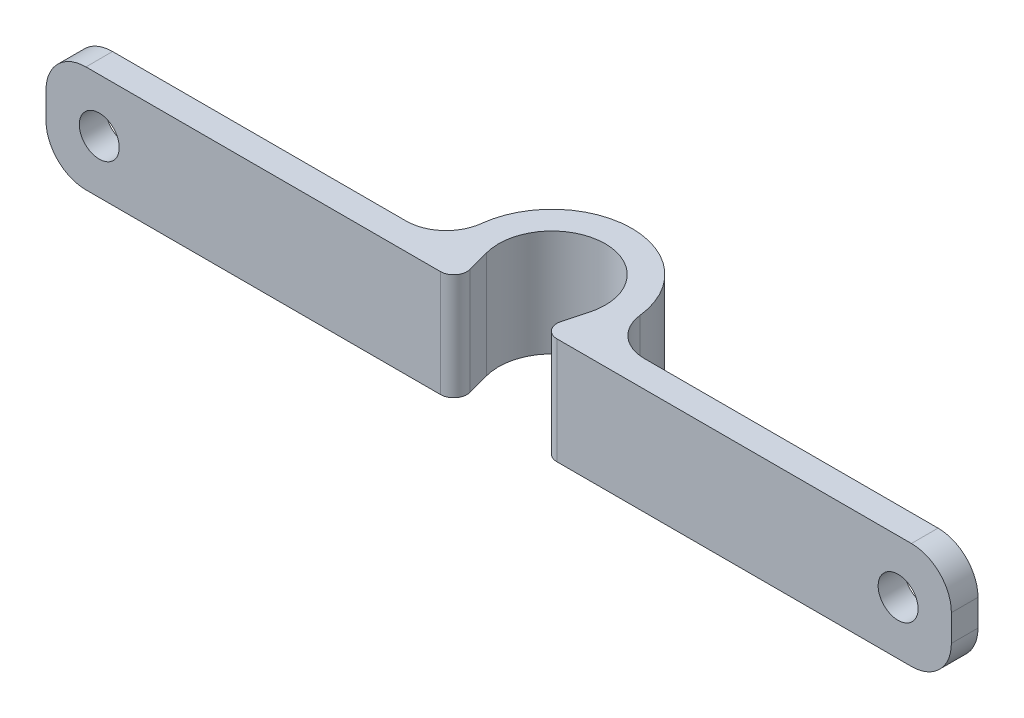
SolidWorks part; units mm, degrees
material "ABS"
ref_plane "Front" through (0, 0, 0) normal (0, 0, 1) x (1, 0, 0)
ref_plane "Top" through (0, 0, 0) normal (0, 1, 0) x (1, 0, 0)
ref_plane "Right" through (0, 0, 0) normal (1, 0, 0) x (0, 0, -1)
sketch "Esquisse1" plane through (0, 0, 0) normal (0, 1, 0) x (1, 0, 0)
  line L0 (-34, 0) -> (-3.0693, 0)
  line L1 (-3.0693, 0) -> (-3.8637, 2.9647)
  line L2 (3.8637, 2.9647) -> (3.0693, 0)
  line L3 (3.0693, 0) -> (34, 0)
  arc A0 (-3.8637, 2.9647) -> (3.8637, 2.9647) centre (0, 4) cw
  dimension "D1" = 4
  dimension "D2" = 4
  dimension "D3" = 68
  dimension "D4" = 30
extrude "Extru.-Mince1" add sketch "Esquisse1" along normal mid plane 8 thin thin type one direction reverse wall 2
fillet "Congé1" radius 1 2 edges at (3.0693, 0, 0) (-3.0693, 0, 0)
fillet "Congé2" radius 3 6 edges at (34, -4, -1) (34, 4, -1) (5.6758, 0, -2) (-34, -4, -1) (-34, 4, -1) (-5.6758, 0, -2)
sketch "Esquisse2" plane through (0, 0, -2) normal (0, 0, -1) x (-1, 0, 0)
  line L0 (0, 50) -> (0, -50) construction
  circle A0 centre (-30, 0) radius 1.5
  circle A1 centre (30, 0) radius 1.5
  point P6 (0, 0)
  dimension "D1" = 3
  dimension "D2" = 60
extrude "Enlèv. mat.-Extru.1" cut sketch "Esquisse2" against normal through all
